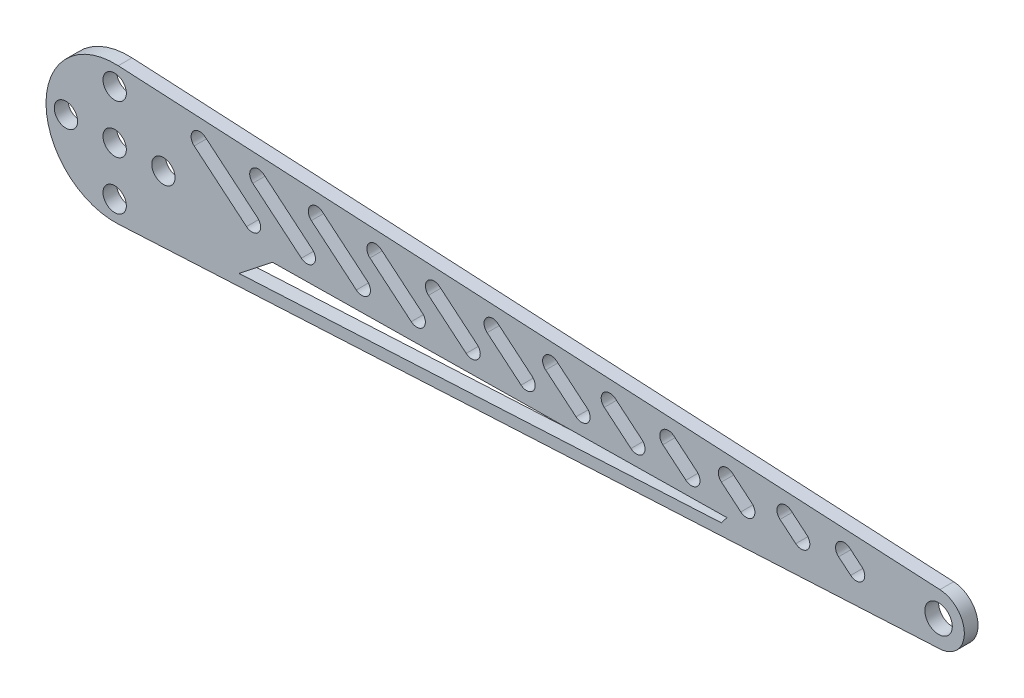
SolidWorks part; units mm, degrees
ref_plane "前视基准面" through (0, 0, 0) normal (0, 0, 1) x (1, 0, 0)
ref_plane "上视基准面" through (0, 0, 0) normal (0, 1, 0) x (1, 0, 0)
ref_plane "右视基准面" through (0, 0, 0) normal (1, 0, 0) x (0, 0, -1)
sketch "草图2" plane through (0, 0, 0) normal (0, 0, 1) x (1, 0, 0)
  line L0 (0, 0) -> (120, 0) construction
  line L1 (120.1953, 3.7449) -> (0.5208, 9.9864)
  line L2 (0.5208, -9.9864) -> (120.1953, -3.7449)
  line L4 (20.0049, 0) -> (12.3904, 6.3633) construction
  line L7 (19.1996, -0.9637) -> (11.585, 5.3996)
  line L8 (20.8102, 0.9637) -> (13.1957, 7.327)
  line L20 (28, 0) -> (20.9176, 5.9186) construction
  line L21 (27.1984, -0.9592) -> (20.1161, 4.9594)
  line L22 (28.8016, 0.9592) -> (21.7192, 6.8777)
  line L23 (36, 0) -> (29.4501, 5.4736) construction
  line L24 (35.1984, -0.9592) -> (28.6486, 4.5144)
  line L25 (36.8016, 0.9592) -> (30.2517, 6.4327)
  line L26 (44, 0) -> (37.9826, 5.0286) construction
  line L27 (43.1984, -0.9592) -> (37.1811, 4.0694)
  line L28 (44.8016, 0.9592) -> (38.7842, 5.9877)
  line L29 (52, 0) -> (46.5152, 4.5836) construction
  line L30 (51.1984, -0.9592) -> (45.7136, 3.6244)
  line L31 (52.8016, 0.9592) -> (47.3167, 5.5427)
  line L32 (60, 0) -> (55.0477, 4.1386) construction
  line L33 (59.1984, -0.9592) -> (54.2461, 3.1794)
  line L34 (60.8016, 0.9592) -> (55.8492, 5.0977)
  line L35 (68, 0) -> (63.5802, 3.6935) construction
  line L36 (67.1984, -0.9592) -> (62.7786, 2.7344)
  line L37 (68.8016, 0.9592) -> (64.3817, 4.6527)
  line L38 (76, 0) -> (72.1127, 3.2485) construction
  line L39 (75.1984, -0.9592) -> (71.3111, 2.2894)
  line L40 (76.8016, 0.9592) -> (72.9142, 4.2077)
  line L41 (84, 0) -> (80.6452, 2.8035) construction
  line L42 (83.1984, -0.9592) -> (79.8436, 1.8444)
  line L43 (84.8016, 0.9592) -> (81.4467, 3.7627)
  line L44 (92, 0) -> (89.1777, 2.3585) construction
  line L45 (91.1984, -0.9592) -> (88.3761, 1.3994)
  line L46 (92.8016, 0.9592) -> (89.9793, 3.3177)
  line L47 (100, 0) -> (97.7102, 1.9135) construction
  line L48 (99.1984, -0.9592) -> (96.9087, 0.9544)
  line L49 (100.8016, 0.9592) -> (98.5118, 2.8727)
  line L50 (108, 0) -> (106.2427, 1.4685) construction
  line L51 (107.1984, -0.9592) -> (105.4412, 0.5093)
  line L52 (108.8016, 0.9592) -> (107.0443, 2.4277)
  line L53 (22.9857, -3.574) -> (89.1777, -2.6855)
  line L55 (89.1777, -2.6855) -> (88.3761, -3.7449)
  line L56 (88.3761, -3.7449) -> (18.1321, -7.4084)
  line L57 (18.1321, -7.4084) -> (22.9857, -3.574)
  circle A0 centre (0, 7.1) radius 1.7
  circle A1 centre (0, 0) radius 1.7
  circle A2 centre (7.1, 0) radius 1.7
  circle A3 centre (-7.1, 0) radius 1.7
  circle A4 centre (0, -7.1) radius 1.7
  arc A5 (0.5208, 9.9864) -> (0.5208, -9.9864) centre (0, 0) ccw
  circle A6 centre (120, 0) radius 2
  arc A7 (120.1953, -3.7449) -> (120.1953, 3.7449) centre (120, 0) ccw
  arc A8 (19.1996, -0.9637) -> (20.8102, 0.9637) centre (20.0049, 0) ccw
  arc A9 (13.1957, 7.327) -> (11.585, 5.3996) centre (12.3904, 6.3633) ccw
  arc A10 (27.1984, -0.9592) -> (28.8016, 0.9592) centre (28, 0) ccw
  arc A11 (21.7192, 6.8777) -> (20.1161, 4.9594) centre (20.9176, 5.9186) ccw
  arc A12 (35.1984, -0.9592) -> (36.8016, 0.9592) centre (36, 0) ccw
  arc A13 (30.2517, 6.4327) -> (28.6486, 4.5144) centre (29.4501, 5.4736) ccw
  arc A14 (43.1984, -0.9592) -> (44.8016, 0.9592) centre (44, 0) ccw
  arc A15 (38.7842, 5.9877) -> (37.1811, 4.0694) centre (37.9826, 5.0286) ccw
  arc A16 (51.1984, -0.9592) -> (52.8016, 0.9592) centre (52, 0) ccw
  arc A17 (47.3167, 5.5427) -> (45.7136, 3.6244) centre (46.5152, 4.5836) ccw
  arc A18 (59.1984, -0.9592) -> (60.8016, 0.9592) centre (60, 0) ccw
  arc A19 (55.8492, 5.0977) -> (54.2461, 3.1794) centre (55.0477, 4.1386) ccw
  arc A20 (67.1984, -0.9592) -> (68.8016, 0.9592) centre (68, 0) ccw
  arc A21 (64.3817, 4.6527) -> (62.7786, 2.7344) centre (63.5802, 3.6935) ccw
  arc A22 (75.1984, -0.9592) -> (76.8016, 0.9592) centre (76, 0) ccw
  arc A23 (72.9142, 4.2077) -> (71.3111, 2.2894) centre (72.1127, 3.2485) ccw
  arc A24 (83.1984, -0.9592) -> (84.8016, 0.9592) centre (84, 0) ccw
  arc A25 (81.4467, 3.7627) -> (79.8436, 1.8444) centre (80.6452, 2.8035) ccw
  arc A26 (91.1984, -0.9592) -> (92.8016, 0.9592) centre (92, 0) ccw
  arc A27 (89.9793, 3.3177) -> (88.3761, 1.3994) centre (89.1777, 2.3585) ccw
  arc A28 (99.1984, -0.9592) -> (100.8016, 0.9592) centre (100, 0) ccw
  arc A29 (98.5118, 2.8727) -> (96.9087, 0.9544) centre (97.7102, 1.9135) ccw
  arc A30 (107.1984, -0.9592) -> (108.8016, 0.9592) centre (108, 0) ccw
  arc A31 (107.0443, 2.4277) -> (105.4412, 0.5093) centre (106.2427, 1.4685) ccw
  point P4 (0, 0)
  point P8 (0, 0)
  point P21 (16.1976, 3.1817)
  point P42 (24.4588, 2.9593)
  point P50 (32.7251, 2.7368)
  point P56 (40.9913, 2.5143)
  point P62 (49.2576, 2.2918)
  point P68 (57.5238, 2.0693)
  point P74 (65.7901, 1.8468)
  point P80 (74.0563, 1.6243)
  point P86 (82.3226, 1.4018)
  point P92 (90.5889, 1.1793)
  point P98 (98.8551, 0.9568)
  point P104 (107.1214, 0.7343)
extrude "凸台-拉伸1" add sketch "草图2" along normal blind 2
